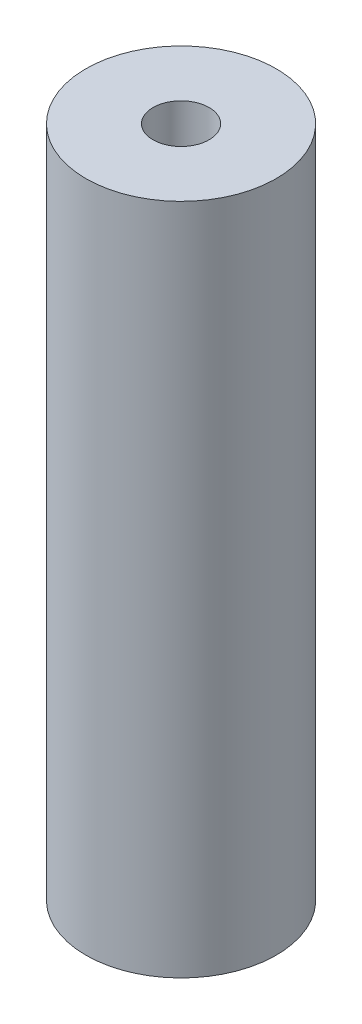
SolidWorks part; units mm, degrees
material "TRT Pourable"
ref_plane "Front Plane" through (0, 0, 0) normal (0, 0, 1) x (1, 0, 0)
ref_plane "Top Plane" through (0, 0, 0) normal (0, 1, 0) x (1, 0, 0)
ref_plane "Right Plane" through (0, 0, 0) normal (1, 0, 0) x (0, 0, -1)
sketch "Sketch1" plane through (0, 0, 0) normal (0, 1, 0) x (1, 0, 0)
  circle A0 centre (0, 0) radius 64.7065
  circle A1 centre (0, 0) radius 19.05
  dimension "D1" = 129.413
  dimension "D2" = 38.1
extrude "Boss-Extrude1" add sketch "Sketch1" along normal blind 457.2
